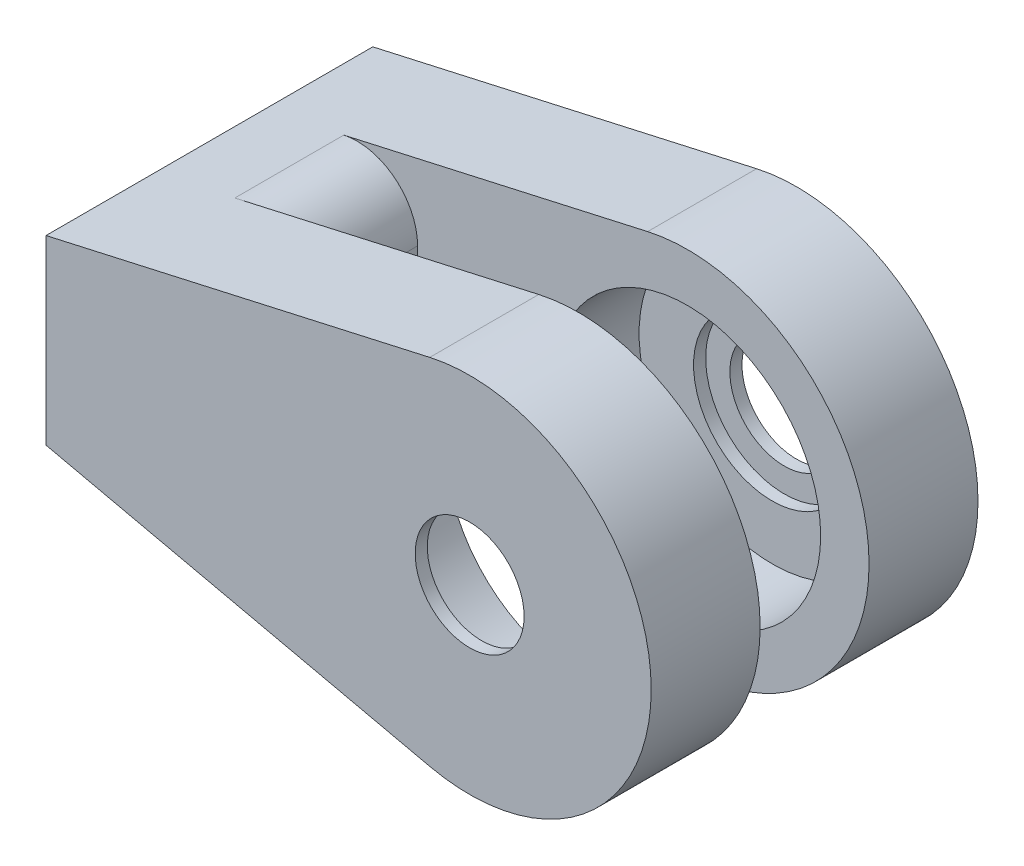
SolidWorks part; units mm, degrees
ref_plane "Front Plane" through (0, 0, 0) normal (0, 0, 1) x (1, 0, 0)
ref_plane "Top Plane" through (0, 0, 0) normal (0, 1, 0) x (1, 0, 0)
ref_plane "Right Plane" through (0, 0, 0) normal (1, 0, 0) x (0, 0, -1)
sketch "Sketch1" plane through (0, 0, 0) normal (0, 0, 1) x (1, 0, 0)
  line L0 (-3.2927, 14.6341) -> (-35, 7.5)
  line L3 (-35, 7.5) -> (-35, -7.5)
  line L4 (-35, -7.5) -> (-3.2927, -14.6341)
  circle A2 centre (0, 0) radius 11 construction
  circle A3 centre (0, 0) radius 15
  dimension "D1" = 30
  dimension "D3" = 22
  dimension "D2" = 15
  dimension "D4" = 50
extrude "Boss-Extrude1" add sketch "Sketch1" along normal blind 9 contours A3 L0 L3 L4 | A3
sketch "Sketch2" plane through (0, 0, 9) normal (0, 0, 1) x (1, 0, 0)
  circle A0 centre (0, 0) radius 11
  dimension "D1" = 22
extrude "Cut-Extrude1" cut sketch "Sketch2" against normal offset from surface (7 mm away) 2 up to face at (-14.5732, 0, 0)
sketch "Sketch3" plane through (0, 0, 2) normal (0, 0, 1) x (1, 0, 0)
  circle A0 centre (0, 0) radius 4.5
  dimension "D1" = 9
extrude "Cut-Extrude2" cut sketch "Sketch3" against normal up to next contours A0
sketch "Sketch4" plane through (0, 0, 9) normal (0, 0, 1) x (1, 0, 0)
  line L0 (-35, -7.5) -> (-3.2927, -14.6341) construction
  line L1 (-3.2927, 14.6341) -> (-35, 7.5) construction
  line L2 (-35, 7.5) -> (-35, -7.5) construction
  line L3 (-35, -7.5) -> (-3.2927, -14.6341)
  line L4 (-3.2927, 14.6341) -> (-35, 7.5)
  line L5 (-35, 7.5) -> (-35, -7.5)
  line L6 (-22.3, 10.3575) -> (-22.3, -10.3575)
  dimension "D1" = 12.7
ref_plane "Plane2" through (0, 0, 13.5) normal (0, 0, 1) x (1, 0, 0)
mirror "Mirror8" about plane through (0, 0, 13.5) normal (0, 0, 1) of bodies 103
extrude "Boss-Extrude3" add sketch "Sketch4" along normal up to next contours L6 L4 L5 L3
sketch "Sketch6" plane through (-35, 0, 0) normal (-1, 0, 0) x (0, 0, 1)
  line L1 (13.5, -16.5) -> (13.5, 16.5) construction
  circle A0 centre (13.5, 0) radius 5.0313
  circle A1 centre (13.5, 0) radius 4.0313
  circle A2 centre (13.5, 0) radius 6.5313
  dimension "D1" = 10.0625
  dimension "D2" = 1
  dimension "D3" = 1.5
extrude "Cut-Extrude3" cut sketch "Sketch6" against normal blind 11.43
fillet "Fillet1" radius 5 2 edges at (-22.3, 10.3575, 13.5) (-22.3, -10.3575, 13.5)
sketch "Sketch7" plane through (0, 0, 25) normal (0, 0, 1) x (1, 0, 0)
  circle A0 centre (0, 0) radius 6.5
  dimension "D1" = 13
extrude "Cut-Extrude4" cut sketch "Sketch7" along normal blind 1 and the other way offset from surface (24 mm away) 1 contours A0 other way up to face at (4.5, 0, 2)
